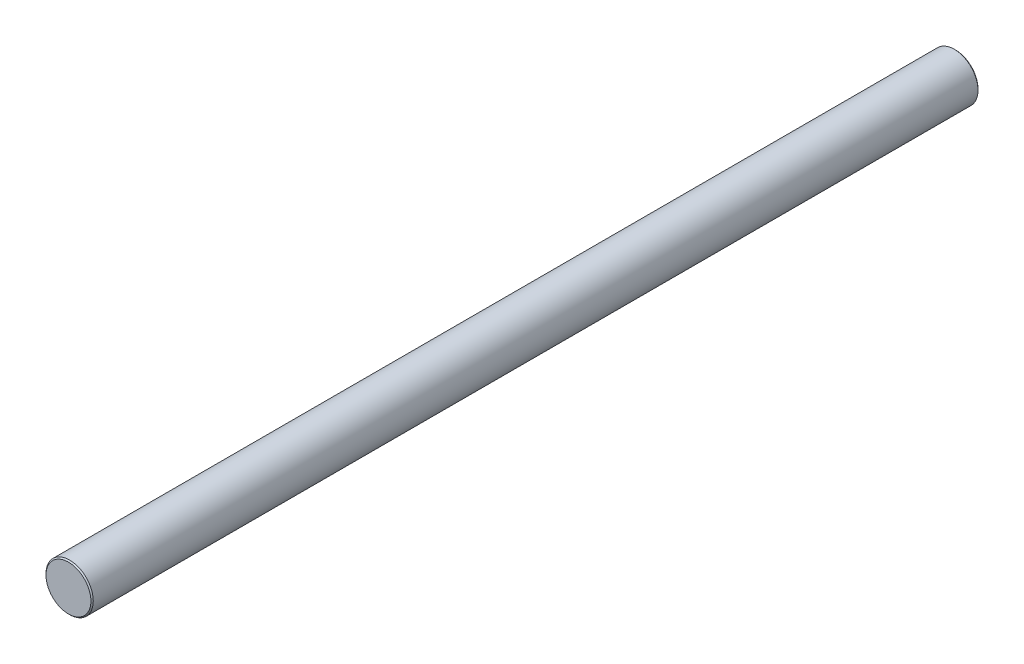
SolidWorks part; units mm, degrees
ref_plane "Front Plane" through (0, 0, 0) normal (0, 0, 1) x (1, 0, 0)
ref_plane "Top Plane" through (0, 0, 0) normal (0, 1, 0) x (1, 0, 0)
ref_plane "Right Plane" through (0, 0, 0) normal (1, 0, 0) x (0, 0, -1)
sketch "Sketch1" plane through (0, 0, 0) normal (0, 0, 1) x (1, 0, 0)
  circle A0 centre (0, 0) radius 4
  dimension "D1" = 8
extrude "Boss-Extrude1" add sketch "Sketch1" along normal blind 150
chamfer "Chamfer1" distance 0.2 angle 45 2 edges at (4, 0, 150) (4, 0, 0)
